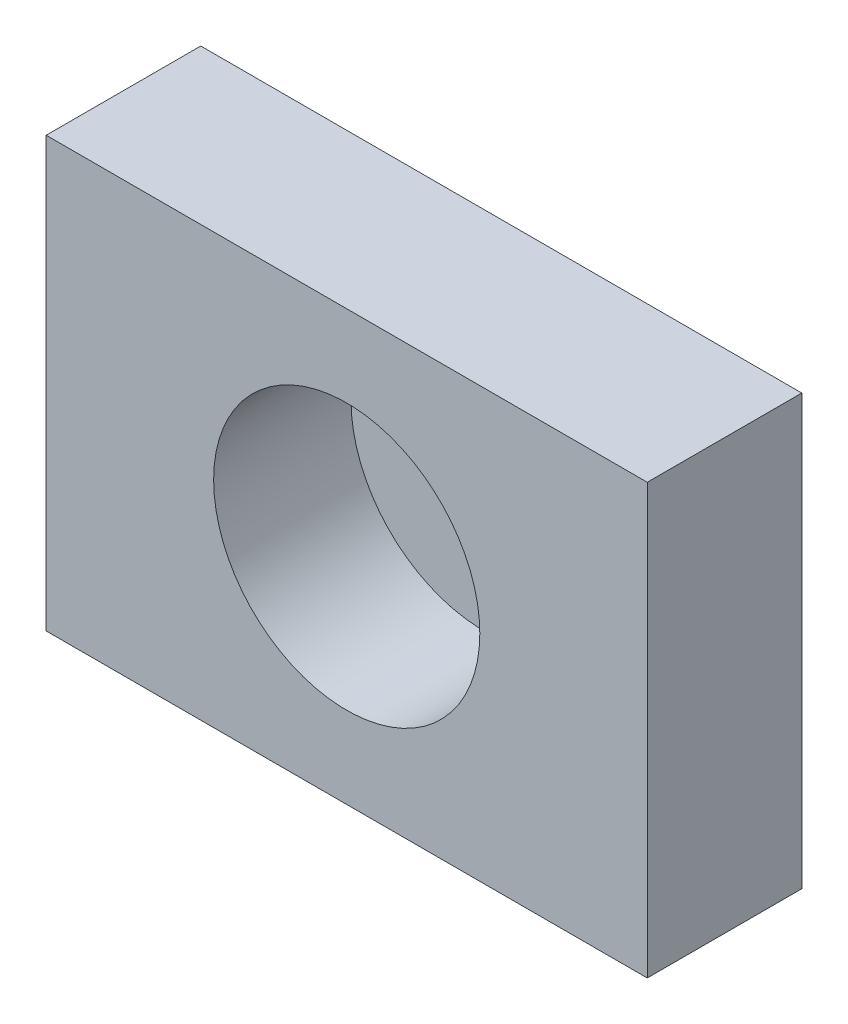
SolidWorks part; units mm, degrees
ref_plane "前视基准面" through (0, 0, 0) normal (0, 0, 1) x (1, 0, 0)
ref_plane "上视基准面" through (0, 0, 0) normal (0, 1, 0) x (1, 0, 0)
ref_plane "右视基准面" through (0, 0, 0) normal (1, 0, 0) x (0, 0, -1)
other "Configuration Table"
sketch "草图1" plane through (0, 0, 0) normal (0, 0, 1) x (1, 0, 0)
  line L0 (0, 0) -> (70, 0)
  line L1 (70, 0) -> (70, 50)
  line L2 (70, 50) -> (0, 50)
  line L3 (0, 50) -> (0, 0)
  circle A0 centre (35, 25) radius 15.5
extrude "凸台-拉伸1" add sketch "草图1" along normal blind 18 flip side to cut
sketch "草图2" plane through (0, 0, 0) normal (0, 0, 1) x (1, 0, 0)
  circle A0 centre (35, 25) radius 15.5
extrude "凸台-拉伸2" add sketch "草图2" along normal blind 2 flip side to cut
